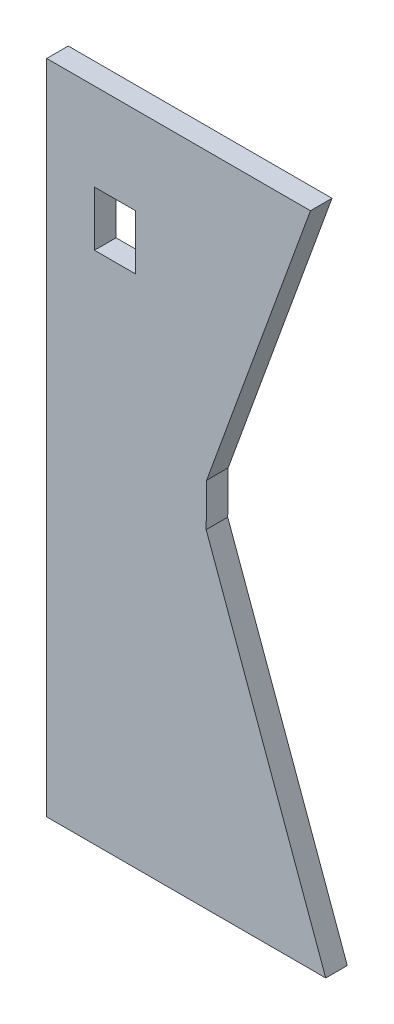
SolidWorks part; units mm, degrees
ref_plane "Front Plane" through (0, 0, 0) normal (1, 0, 0) x (0, 1, 0)
ref_plane "Top Plane" through (0, 0, 0) normal (0, 0, 1) x (0, 1, 0)
ref_plane "Right Plane" through (0, 0, 0) normal (0, 1, 0) x (-1, 0, 0)
sketch "Sketch1" plane through (0, 0, 0) normal (0, 0, 1) x (0, 1, 0)
  line L0 (-152.4, 64.7407) -> (152.4, 64.7407)
  line L1 (152.4, 64.7407) -> (152.4, -57.6505)
  line L2 (0.0396, -9.2573) -> (19.9925, -9.4581)
  line L3 (19.9925, -9.4581) -> (152.4, -57.6505)
  line L4 (-152.4, 64.7407) -> (-152.4, -64.7407)
  line L5 (0.0396, -9.2573) -> (-152.4, -64.7407)
  line L7 (86.407, 42.5605) -> (111.807, 42.5605)
  line L8 (86.407, 42.5605) -> (86.407, 23.5105)
  line L9 (86.407, 23.5105) -> (111.807, 23.5105)
  line L10 (111.807, 42.5605) -> (111.807, 23.5105)
  dimension "D1" = 304.8
  dimension "D2" = 19.05
  dimension "D3" = 25.4
extrude "Boss-Extrude1" add sketch "Sketch1" along normal blind 10
